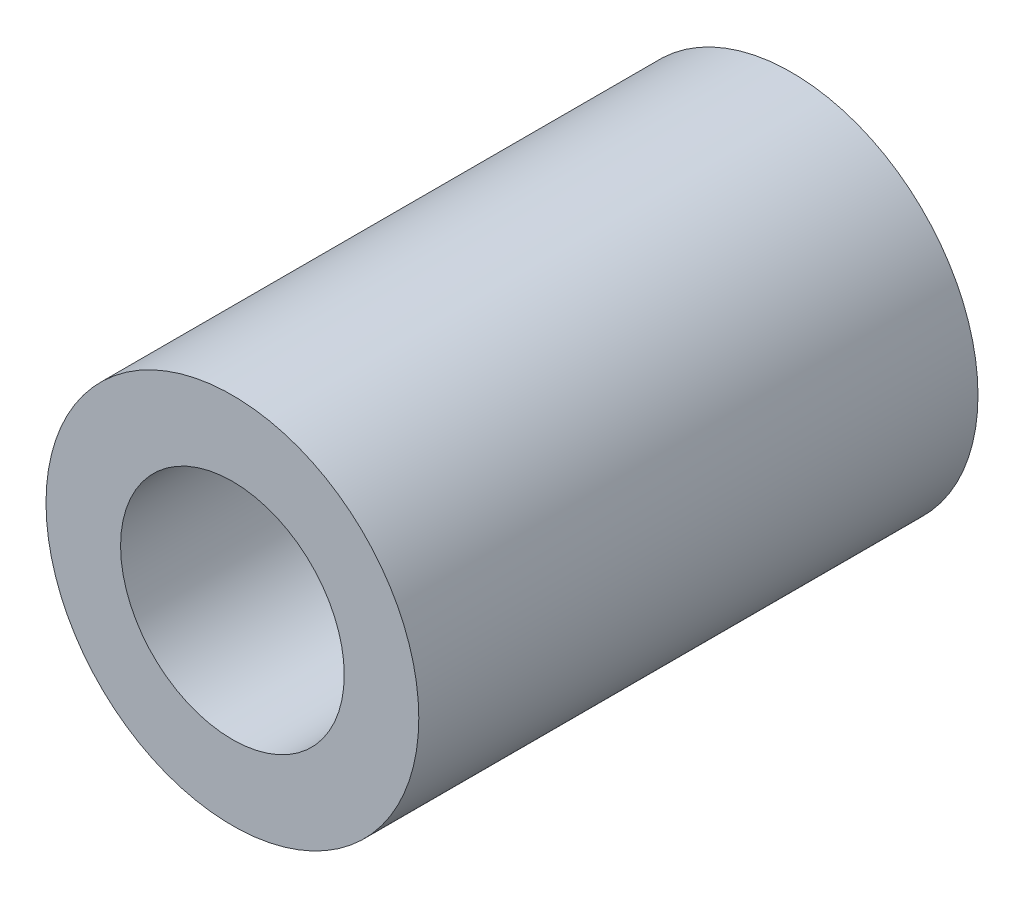
SolidWorks part; units mm, degrees
ref_plane "前视基准面" through (0, 0, 0) normal (0, 0, 1) x (1, 0, 0)
ref_plane "上视基准面" through (0, 0, 0) normal (0, 1, 0) x (1, 0, 0)
ref_plane "右视基准面" through (0, 0, 0) normal (1, 0, 0) x (0, 0, -1)
other "Configuration Table"
sketch "草图1" plane through (0, 0, 0) normal (0, 0, 1) x (1, 0, 0)
  circle A0 centre (0, 0) radius 10
  circle A1 centre (0, 0) radius 6
  dimension "D1" = 20
extrude "凸台-拉伸1" add sketch "草图1" along normal mid plane 30
